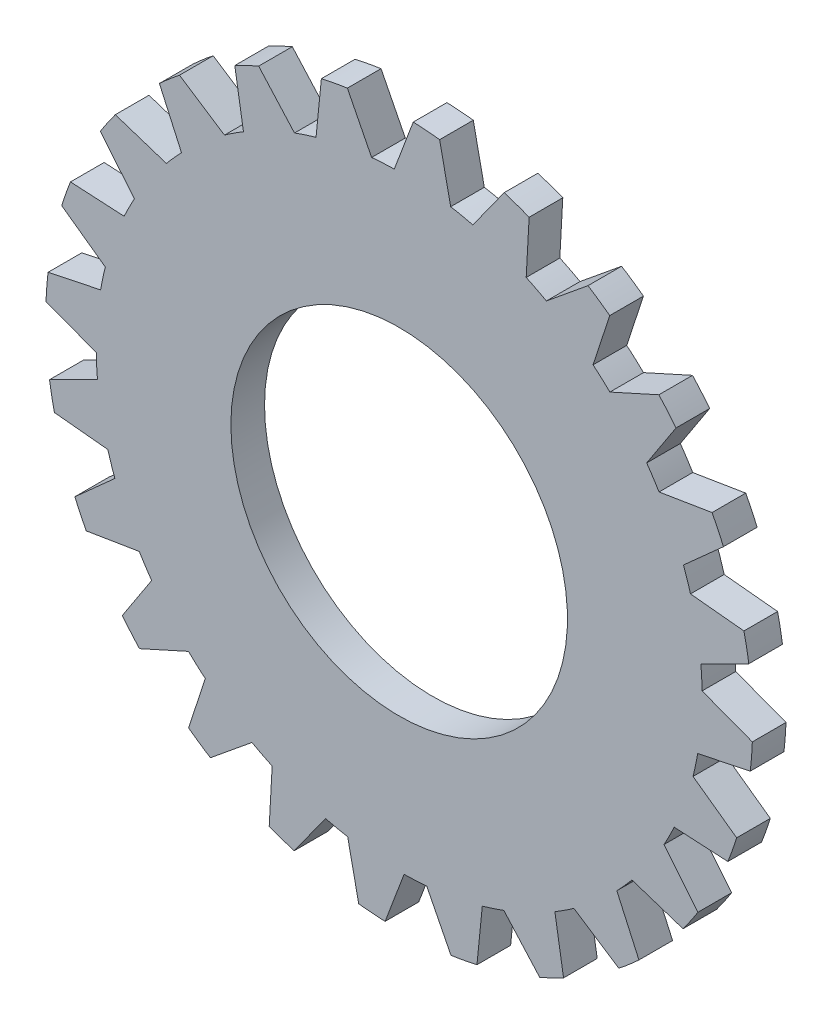
SolidWorks part; units mm, degrees
ref_plane "前视基准面" through (0, 0, 0) normal (0, 0, 1) x (1, 0, 0)
ref_plane "上视基准面" through (0, 0, 0) normal (0, 1, 0) x (1, 0, 0)
ref_plane "右视基准面" through (0, 0, 0) normal (1, 0, 0) x (0, 0, -1)
sketch "草图1" plane through (0, 0, 0) normal (0, 0, 1) x (1, 0, 0)
  line L0 (-493.9568, 1730.8976) -> (0, 0) construction
  line L1 (0, 0) -> (-29.1364, 1799.7642) construction
  line L2 (0, 0) -> (-222.6562, 2440.3538) construction
  line L3 (0, 0) -> (-29.1364, 1799.7642) construction
  line L4 (0, 0) -> (-129.3958, 2412.3516) construction
  line L5 (0, 0) -> (-333.3935, 2250.2677) construction
  line L6 (0, 0) -> (-525.0387, 2326.4706) construction
  line L7 (-462.302, 2048.4816) -> (-493.9568, 1730.8976)
  line L8 (-307.7707, 2077.3245) -> (-163.5514, 1792.5543)
  line L9 (83.6366, 2098.3338) -> (-29.1364, 1799.7642)
  line L10 (240.3675, 2086.1983) -> (305.9686, 1773.8047)
  line L11 (623.8755, 2005.1881) -> (437.6697, 1745.9797)
  line L12 (772.125, 1952.9012) -> (754.6374, 1634.1733)
  line L13 (1121.5983, 1775.3921) -> (874.6492, 1573.2097)
  line L14 (1251.2635, 1686.517) -> (1151.879, 1383.1756)
  line L15 (1542.8861, 1424.6061) -> (1252.0229, 1293.228)
  line L16 (1645.1305, 1305.1995) -> (1470.6218, 1037.9169)
  line L17 (1859.0287, 976.7355) -> (1544.0733, 925.1149)
  line L18 (1926.8845, 834.9348) -> (1689.1443, 621.9258)
  line L19 (2048.4816, 462.302) -> (1730.8976, 493.9568)
  line L20 (2077.3245, 307.7707) -> (1792.5543, 163.5514)
  line L21 (2098.3338, -83.6366) -> (1799.7642, 29.1364)
  line L22 (2086.1983, -240.3675) -> (1773.8047, -305.9686)
  line L23 (2005.1881, -623.8755) -> (1745.9797, -437.6697)
  line L24 (1952.9012, -772.125) -> (1634.1733, -754.6374)
  line L25 (1775.3921, -1121.5983) -> (1573.2097, -874.6492)
  line L26 (1686.517, -1251.2635) -> (1383.1756, -1151.879)
  line L27 (1424.6061, -1542.8861) -> (1293.228, -1252.0229)
  line L28 (1305.1995, -1645.1305) -> (1037.9169, -1470.6218)
  line L29 (976.7355, -1859.0287) -> (925.1149, -1544.0733)
  line L30 (834.9348, -1926.8845) -> (621.9258, -1689.1443)
  line L31 (462.302, -2048.4816) -> (493.9568, -1730.8976)
  line L32 (307.7707, -2077.3245) -> (163.5514, -1792.5543)
  line L33 (-83.6366, -2098.3338) -> (29.1364, -1799.7642)
  line L34 (-240.3675, -2086.1983) -> (-305.9686, -1773.8047)
  line L35 (-623.8755, -2005.1881) -> (-437.6697, -1745.9797)
  line L36 (-772.125, -1952.9012) -> (-754.6374, -1634.1733)
  line L37 (-1121.5983, -1775.3921) -> (-874.6492, -1573.2097)
  line L38 (-1251.2635, -1686.517) -> (-1151.879, -1383.1756)
  line L39 (-1542.8861, -1424.6061) -> (-1252.0229, -1293.228)
  line L40 (-1645.1305, -1305.1995) -> (-1470.6218, -1037.9169)
  line L41 (-1859.0287, -976.7355) -> (-1544.0733, -925.1149)
  line L42 (-1926.8845, -834.9348) -> (-1689.1443, -621.9258)
  line L43 (-2048.4816, -462.302) -> (-1730.8976, -493.9568)
  line L44 (-2077.3245, -307.7707) -> (-1792.5543, -163.5514)
  line L45 (-2098.3338, 83.6366) -> (-1799.7642, -29.1364)
  line L46 (-2086.1983, 240.3675) -> (-1773.8047, 305.9686)
  line L47 (-2005.1881, 623.8755) -> (-1745.9797, 437.6697)
  line L48 (-1952.9012, 772.125) -> (-1634.1733, 754.6374)
  line L49 (-1775.3921, 1121.5983) -> (-1573.2097, 874.6492)
  line L50 (-1686.517, 1251.2635) -> (-1383.1756, 1151.879)
  line L51 (-1424.6061, 1542.8861) -> (-1293.228, 1252.0229)
  line L52 (-1305.1995, 1645.1305) -> (-1037.9169, 1470.6218)
  line L53 (-976.7355, 1859.0287) -> (-925.1149, 1544.0733)
  line L54 (-834.9348, 1926.8845) -> (-621.9258, 1689.1443)
  line L55 (0, 0) -> (-163.5514, 1792.5543) construction
  arc A0 (-163.5514, 1792.5543) -> (-29.1364, 1799.7642) centre (0, 0) cw
  arc A1 (240.3675, 2086.1983) -> (83.6366, 2098.3338) centre (0, 0) ccw
  arc A2 (305.9686, 1773.8047) -> (437.6697, 1745.9797) centre (0, 0) cw
  arc A3 (754.6374, 1634.1733) -> (874.6492, 1573.2097) centre (0, 0) cw
  arc A4 (1151.879, 1383.1756) -> (1252.0229, 1293.228) centre (0, 0) cw
  arc A5 (1470.6218, 1037.9169) -> (1544.0733, 925.1149) centre (0, 0) cw
  arc A6 (1689.1443, 621.9258) -> (1730.8976, 493.9568) centre (0, 0) cw
  arc A7 (1792.5543, 163.5514) -> (1799.7642, 29.1364) centre (0, 0) cw
  arc A8 (1773.8047, -305.9686) -> (1745.9797, -437.6697) centre (0, 0) cw
  arc A9 (1634.1733, -754.6374) -> (1573.2097, -874.6492) centre (0, 0) cw
  arc A10 (1383.1756, -1151.879) -> (1293.228, -1252.0229) centre (0, 0) cw
  arc A11 (1037.9169, -1470.6218) -> (925.1149, -1544.0733) centre (0, 0) cw
  arc A12 (621.9258, -1689.1443) -> (493.9568, -1730.8976) centre (0, 0) cw
  arc A13 (163.5514, -1792.5543) -> (29.1364, -1799.7642) centre (0, 0) cw
  arc A14 (-305.9686, -1773.8047) -> (-437.6697, -1745.9797) centre (0, 0) cw
  arc A15 (-754.6374, -1634.1733) -> (-874.6492, -1573.2097) centre (0, 0) cw
  arc A16 (-1151.879, -1383.1756) -> (-1252.0229, -1293.228) centre (0, 0) cw
  arc A17 (-1470.6218, -1037.9169) -> (-1544.0733, -925.1149) centre (0, 0) cw
  arc A18 (-1689.1443, -621.9258) -> (-1730.8976, -493.9568) centre (0, 0) cw
  arc A19 (-1792.5543, -163.5514) -> (-1799.7642, -29.1364) centre (0, 0) cw
  arc A20 (-1773.8047, 305.9686) -> (-1745.9797, 437.6697) centre (0, 0) cw
  arc A21 (-1634.1733, 754.6374) -> (-1573.2097, 874.6492) centre (0, 0) cw
  arc A22 (-1383.1756, 1151.879) -> (-1293.228, 1252.0229) centre (0, 0) cw
  arc A23 (-1037.9169, 1470.6218) -> (-925.1149, 1544.0733) centre (0, 0) cw
  arc A24 (-621.9258, 1689.1443) -> (-493.9568, 1730.8976) centre (0, 0) cw
  arc A25 (-307.7707, 2077.3245) -> (-462.302, 2048.4816) centre (0, 0) ccw
  arc A26 (772.125, 1952.9012) -> (623.8755, 2005.1881) centre (0, 0) ccw
  arc A27 (1251.2635, 1686.517) -> (1121.5983, 1775.3921) centre (0, 0) ccw
  arc A28 (1645.1305, 1305.1995) -> (1542.8861, 1424.6061) centre (0, 0) ccw
  arc A29 (1926.8845, 834.9348) -> (1859.0287, 976.7355) centre (0, 0) ccw
  arc A30 (2077.3245, 307.7707) -> (2048.4816, 462.302) centre (0, 0) ccw
  arc A31 (2086.1983, -240.3675) -> (2098.3338, -83.6366) centre (0, 0) ccw
  arc A32 (1952.9012, -772.125) -> (2005.1881, -623.8755) centre (0, 0) ccw
  arc A33 (1686.517, -1251.2635) -> (1775.3921, -1121.5983) centre (0, 0) ccw
  arc A34 (1305.1995, -1645.1305) -> (1424.6061, -1542.8861) centre (0, 0) ccw
  arc A35 (834.9348, -1926.8845) -> (976.7355, -1859.0287) centre (0, 0) ccw
  arc A36 (307.7707, -2077.3245) -> (462.302, -2048.4816) centre (0, 0) ccw
  arc A37 (-240.3675, -2086.1983) -> (-83.6366, -2098.3338) centre (0, 0) ccw
  arc A38 (-772.125, -1952.9012) -> (-623.8755, -2005.1881) centre (0, 0) ccw
  arc A39 (-1251.2635, -1686.517) -> (-1121.5983, -1775.3921) centre (0, 0) ccw
  arc A40 (-1645.1305, -1305.1995) -> (-1542.8861, -1424.6061) centre (0, 0) ccw
  arc A41 (-1926.8845, -834.9348) -> (-1859.0287, -976.7355) centre (0, 0) ccw
  arc A42 (-2077.3245, -307.7707) -> (-2048.4816, -462.302) centre (0, 0) ccw
  arc A43 (-2086.1983, 240.3675) -> (-2098.3338, 83.6366) centre (0, 0) ccw
  arc A44 (-1952.9012, 772.125) -> (-2005.1881, 623.8755) centre (0, 0) ccw
  arc A45 (-1686.517, 1251.2635) -> (-1775.3921, 1121.5983) centre (0, 0) ccw
  arc A46 (-1305.1995, 1645.1305) -> (-1424.6061, 1542.8861) centre (0, 0) ccw
  arc A47 (-834.9348, 1926.8845) -> (-976.7355, 1859.0287) centre (0, 0) ccw
  point P13 (-96.4113, 1797.4162)
  point P63 (-2667.6856, 1393.4574)
  dimension "D1" = 5.357
  dimension "D2" = 3.21
  dimension "D3" = 15
  dimension "D4" = 4.286
  dimension "D6" = 1800
  dimension "D7" = 24
  dimension "D8" = 1800
  dimension "D5" = 24
extrude "凸台-拉伸1" add sketch "草图1" along normal blind 200
sketch "草图2" plane through (0, 0, 0) normal (0, 0, -1) x (-1, 0, 0)
  circle A0 centre (0, 0) radius 1000
  dimension "D1" = 2000
extrude "切除-拉伸1" cut sketch "草图2" against normal through all
